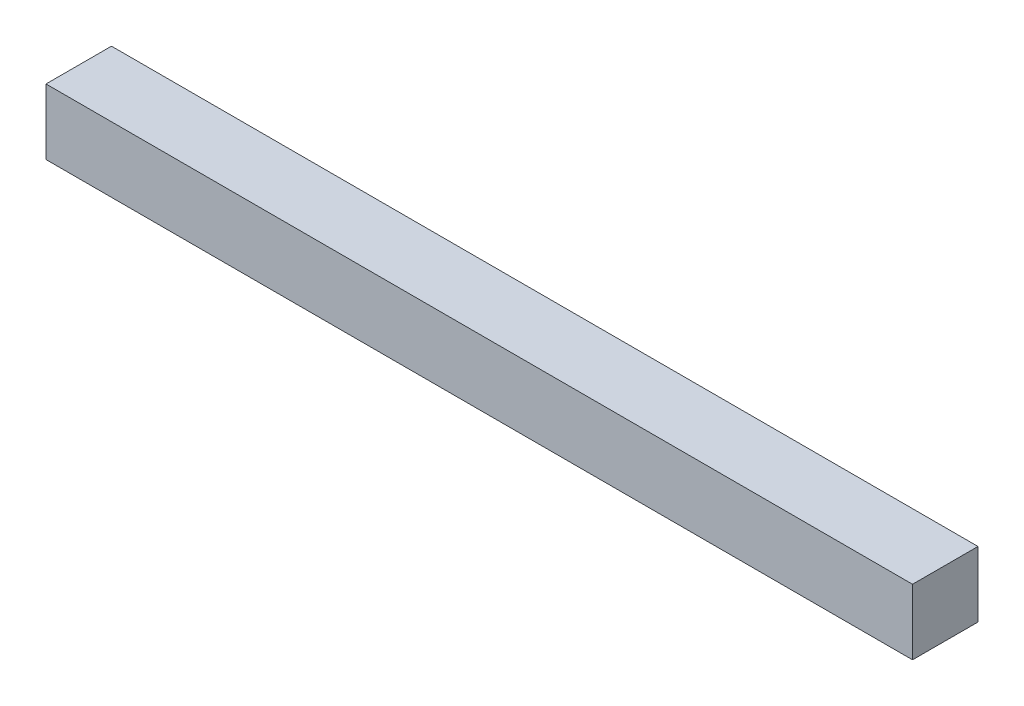
SolidWorks part; units mm, degrees
ref_plane "Front Plane" through (0, 0, 0) normal (0, 0, 1) x (1, 0, 0)
ref_plane "Top Plane" through (0, 0, 0) normal (0, 1, 0) x (1, 0, 0)
ref_plane "Right Plane" through (0, 0, 0) normal (1, 0, 0) x (0, 0, -1)
sketch "Sketch1" plane through (0, 0, 0) normal (1, 0, 0) x (0, 0, -1)
  line L1 (0, 0) -> (15, 0)
  line L2 (0, 0) -> (0, 15)
  line L3 (0, 15) -> (15, 15)
  line L4 (15, 0) -> (15, 15)
  dimension "D1" = 15
extrude "Boss-Extrude1" add sketch "Sketch1" along normal blind 198.52
